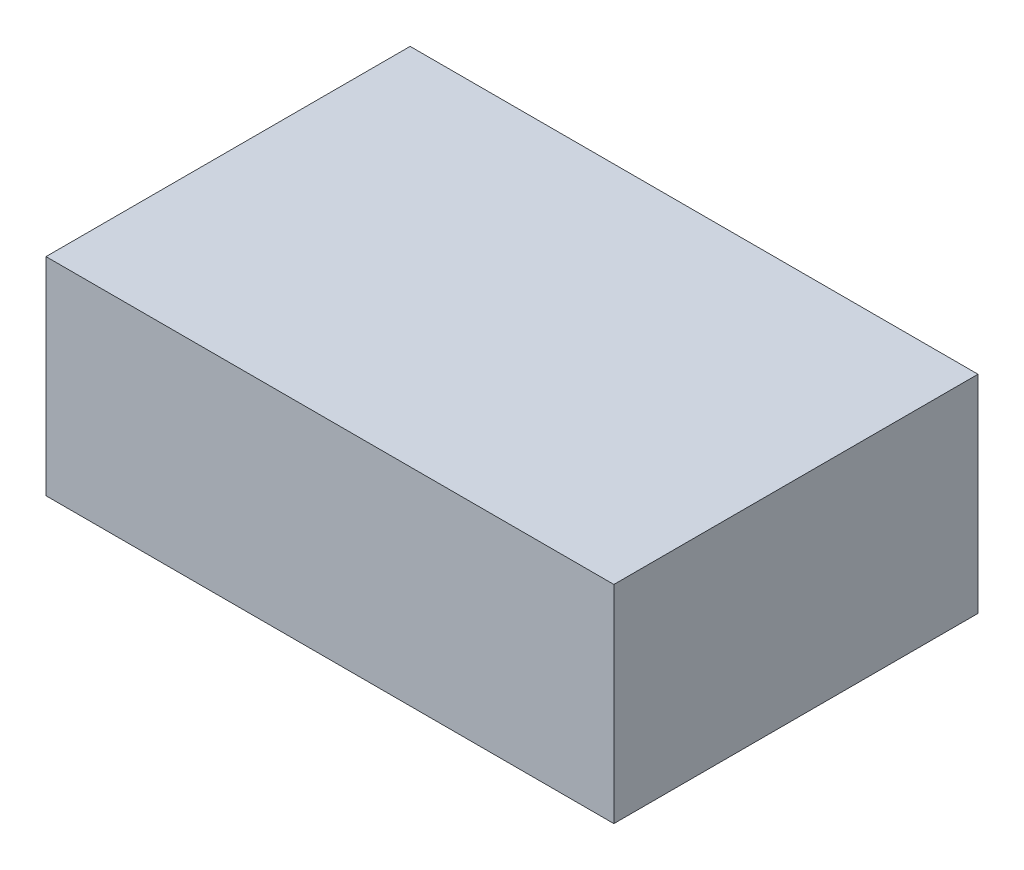
SolidWorks part; units mm, degrees
ref_plane "Plan de face" through (0, 0, 0) normal (0, 0, 1) x (1, 0, 0)
ref_plane "Plan de dessus" through (0, 0, 0) normal (0, 1, 0) x (1, 0, 0)
ref_plane "Plan de droite" through (0, 0, 0) normal (1, 0, 0) x (0, 0, -1)
sketch "Esquisse1" plane through (0, 0, 0) normal (0, 1, 0) x (1, 0, 0)
  line L0 (0, 0) -> (87.4, 0)
  line L1 (87.4, 0) -> (87.4, 56.04)
  line L2 (0, 0) -> (0, 56.04)
  line L3 (0, 56.04) -> (87.4, 56.04)
extrude "Boss.-Extru.1" add sketch "Esquisse1" along normal blind 31.88
